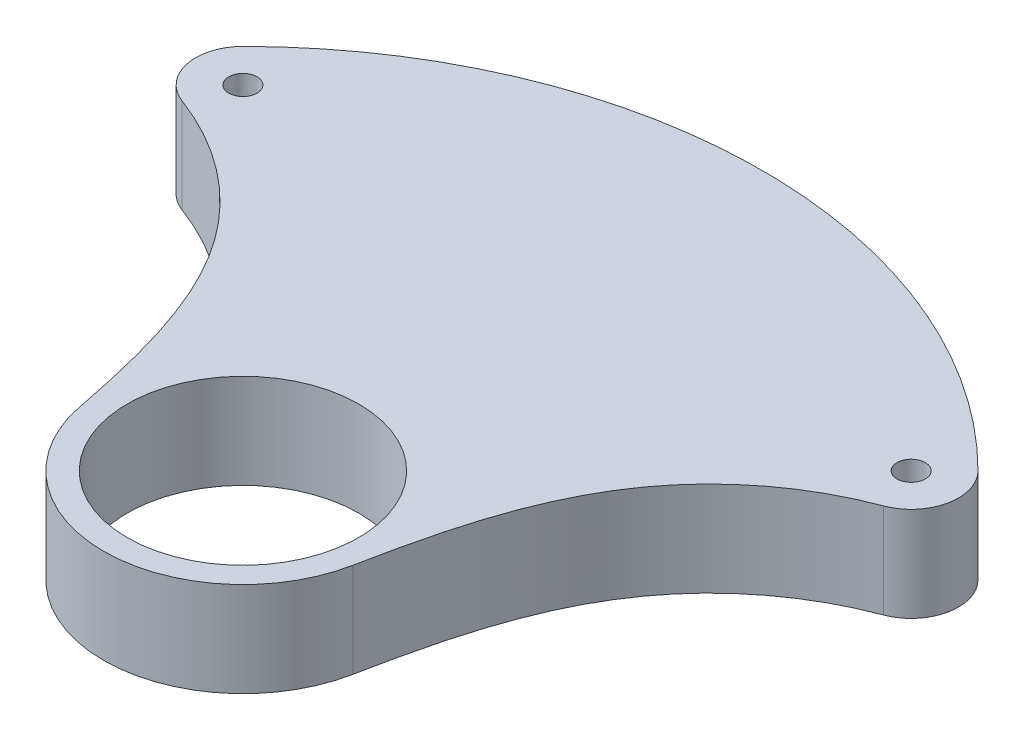
SolidWorks part; units mm, degrees
ref_plane "Front Plane" through (0, 0, 0) normal (0, 0, 1) x (1, 0, 0)
ref_plane "Top Plane" through (0, 0, 0) normal (0, 1, 0) x (1, 0, 0)
ref_plane "Right Plane" through (0, 0, 0) normal (1, 0, 0) x (0, 0, -1)
sketch "Sketch2" plane through (0, 0, 0) normal (0, 1, 0) x (1, 0, 0)
  line L0 (-31.8198, 31.8198) -> (-38.8909, 38.8909)
  line L1 (0, -55) -> (0, 55) construction
  line L2 (14.75, 0) -> (45, 0) construction
  circle A0 centre (0, 0) radius 45 construction
  circle A1 centre (0, 0) radius 55
  arc A2 (-38.8909, 38.8909) -> (-31.8198, 31.8198) centre (-35.3553, 35.3553) ccw
  arc A3 (38.8909, 38.8909) -> (31.8198, 31.8198) centre (35.3553, 35.3553) cw
  circle A4 centre (0, 0) radius 12.25
  circle A5 centre (0, 0) radius 14.75
  circle A6 centre (0, 0) radius 29.875 construction
  spline S0 degree 3 poles (-37.1013, 30.6701) (-31.0879, 28.4292) (-19.5444, 19.3017) (-16.0486, 5.1692) (-14.473, -2.8453) knots 0 0 0 0 0.434164 1 1 1 1
  spline S1 degree 3 poles (37.1013, 30.6701) (31.0879, 28.4292) (19.5444, 19.3017) (16.0486, 5.1692) (14.473, -2.8453) knots 0 0 0 0 0.434164 1 1 1 1
  point P23 (29.875, 0)
  dimension "D2" = 110
  dimension "D4" = 24.5
  dimension "D1" = 10
  dimension "D3" = 45
  dimension "D5" = 2.5
extrude "Boss-Extrude1" add sketch "Sketch2" along normal blind 10
sketch "Sketch3" plane through (0, 10, 0) normal (0, 1, 0) x (1, 0, 0)
  line L0 (0, 0) -> (-35.3553, 35.3553) construction
  line L1 (-35.3553, 35.3553) -> (35.3553, 35.3553) construction
  line L2 (35.3553, 35.3553) -> (0, 0) construction
  line L3 (0, -2.75) -> (0, 2.75) construction
  circle A0 centre (-35.3553, 35.3553) radius 1.5
  circle A1 centre (35.3553, 35.3553) radius 1.5
  dimension "D1" = 3
extrude "Cut-Extrude1" cut sketch "Sketch3" against normal up to next
equation "\"Width\"= 10mm"
equation "\"Thick\"= 10mm"
equation "\"Diameter\"= 110"
equation "\"D2@Sketch2\"= \"Diameter\""
equation "\"DegreeOfArc\"= 90deg"
equation "\"D3@Sketch2\"= \"DegreeOfArc\" / 2"
equation "\"D1@Boss-Extrude1\"= \"Thick\""
equation "\"D1@Sketch2\"= \"Width\""
equation "\"D4@Sketch2\"=24.5"
